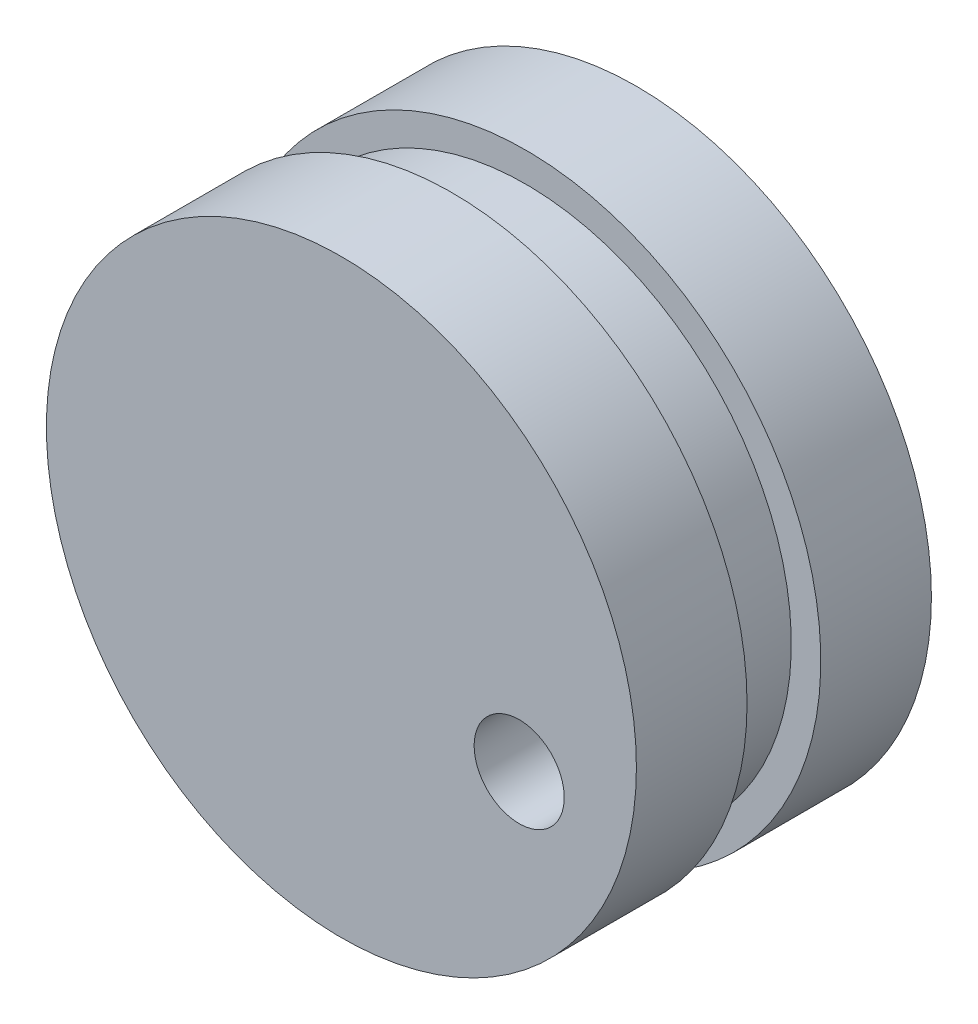
SolidWorks part; units mm, degrees
ref_plane "Front Plane" through (0, 0, 0) normal (0, 0, 1) x (1, 0, 0)
ref_plane "Top Plane" through (0, 0, 0) normal (0, 1, 0) x (1, 0, 0)
ref_plane "Right Plane" through (0, 0, 0) normal (1, 0, 0) x (0, 0, -1)
sketch "Sketch1" plane through (0, 0, 0) normal (0, 0, 1) x (1, 0, 0)
  circle A0 centre (0, 0) radius 20
  dimension "D1" = 40
extrude "Boss-Extrude1" add sketch "Sketch1" along normal blind 20
sketch "Sketch4" plane through (0, 0, 0) normal (1, 0, 0) x (0, 0, -1)
  line L0 (-20, 20) -> (-20, -20) construction
  line L1 (-12.5, 20.9128) -> (-7.5, 20.9128)
  line L2 (-12.5, 20.9128) -> (-12.5, 18)
  line L3 (-12.5, 18) -> (-7.5, 18)
  line L4 (-7.5, 20.9128) -> (-7.5, 18)
  line L5 (0, -20) -> (0, 20) construction
  line L6 (0, 20) -> (-20, 20) construction
  line L7 (0, 0) -> (-28.0219, 0) construction
  dimension "D1" = 7.5
  dimension "D2" = 7.5
  dimension "D3" = 2
revolve "Cut-Revolve1" cut sketch "Sketch4" angle 360 about L7
sketch "Sketch5" plane through (0, 0, 0) normal (0, 0, -1) x (-1, 0, 0)
  circle A0 centre (-12.0525, -4.2182) radius 3.0556
extrude "Cut-Extrude2" cut sketch "Sketch5" against normal through all
